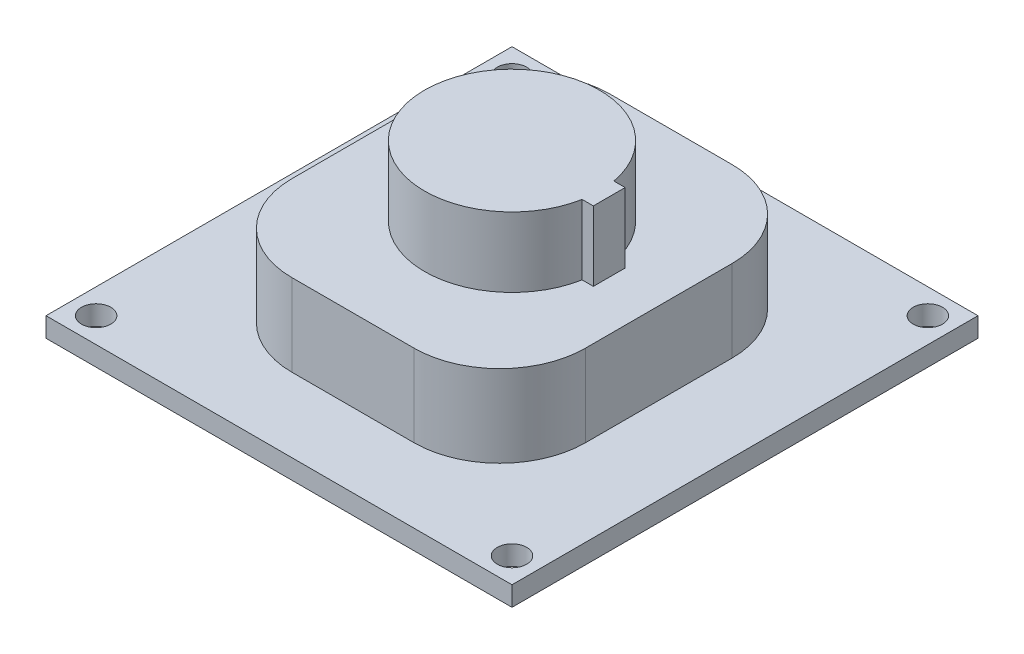
SolidWorks part; units mm, degrees
ref_plane "Front Plane" through (0, 0, 0) normal (0, 0, 1) x (1, 0, 0)
ref_plane "Top Plane" through (0, 0, 0) normal (0, 1, 0) x (1, 0, 0)
ref_plane "Right Plane" through (0, 0, 0) normal (1, 0, 0) x (0, 0, -1)
sketch "Sketch1" plane through (0, 0, 0) normal (0, 1, 0) x (1, 0, 0)
  line L0 (-17, 17) -> (17, 17) construction
  line L1 (-19.05, 19.05) -> (19.05, 19.05)
  line L2 (-19.05, 19.05) -> (-19.05, -19.05)
  line L3 (-19.05, -19.05) -> (19.05, -19.05)
  line L4 (19.05, 19.05) -> (19.05, -19.05)
  line L5 (0, -19.05) -> (0, 19.05) construction
  line L6 (-19.05, 0) -> (19.05, 0) construction
  line L7 (-17, 17) -> (-17, -17) construction
  circle A0 centre (-17, 17) radius 1.2
  circle A1 centre (17, 17) radius 1.2
  circle A2 centre (17, -17) radius 1.2
  circle A3 centre (-17, -17) radius 1.2
  point P4 (-17, 0)
  point P18 (0, 17)
  point P316 (0, 0)
  dimension "D2" = 2.4
  dimension "D5" = 2
  dimension "D1" = 38.1
  dimension "D7" = 34
  dimension "D8" = 34
  dimension "D6" = 2
extrude "Boss-Extrude1" add sketch "Sketch1" along normal blind 1.6
sketch "Sketch2" plane through (0, 1.6, 0) normal (0, 1, 0) x (1, 0, 0)
  line L1 (-5, 13) -> (5, 13)
  line L2 (-12, 6) -> (-12, -6)
  line L3 (-5, -13) -> (5, -13)
  line L4 (12, 6) -> (12, -6)
  line L5 (0, -13) -> (0, 13) construction
  line L6 (-12, 0) -> (12, 0) construction
  arc A0 (5, 13) -> (12, 6) centre (5, 6) cw
  arc A1 (5, -13) -> (12, -6) centre (5, -6) ccw
  arc A2 (-12, -6) -> (-5, -13) centre (-5, -6) ccw
  arc A3 (-5, 13) -> (-12, 6) centre (-5, 6) ccw
  point P8 (12, 13)
  point P11 (12, -13)
  point P16 (-12, 13)
  point P132 (0, 0)
  dimension "D3" = 7
  dimension "D1" = 24
  dimension "D2" = 26
extrude "Boss-Extrude2" add sketch "Sketch2" along normal blind 6.7
sketch "Sketch3" plane through (0, 8.3, 0) normal (0, 1, 0) x (1, 0, 0)
  line L1 (7.0308, 1.3) -> (7.95, 1.3)
  line L3 (7.0308, -1.3) -> (7.95, -1.3)
  line L4 (7.95, 1.3) -> (7.95, -1.3)
  line L6 (-7.15, 0) -> (7.95, 0) construction
  arc A0 (7.0308, 1.3) -> (7.0308, -1.3) centre (0, 0) ccw
  dimension "D1" = 14.3
  dimension "D2" = 15.1
  dimension "D3" = 2.6
extrude "Boss-Extrude3" add sketch "Sketch3" along normal blind 5.7
